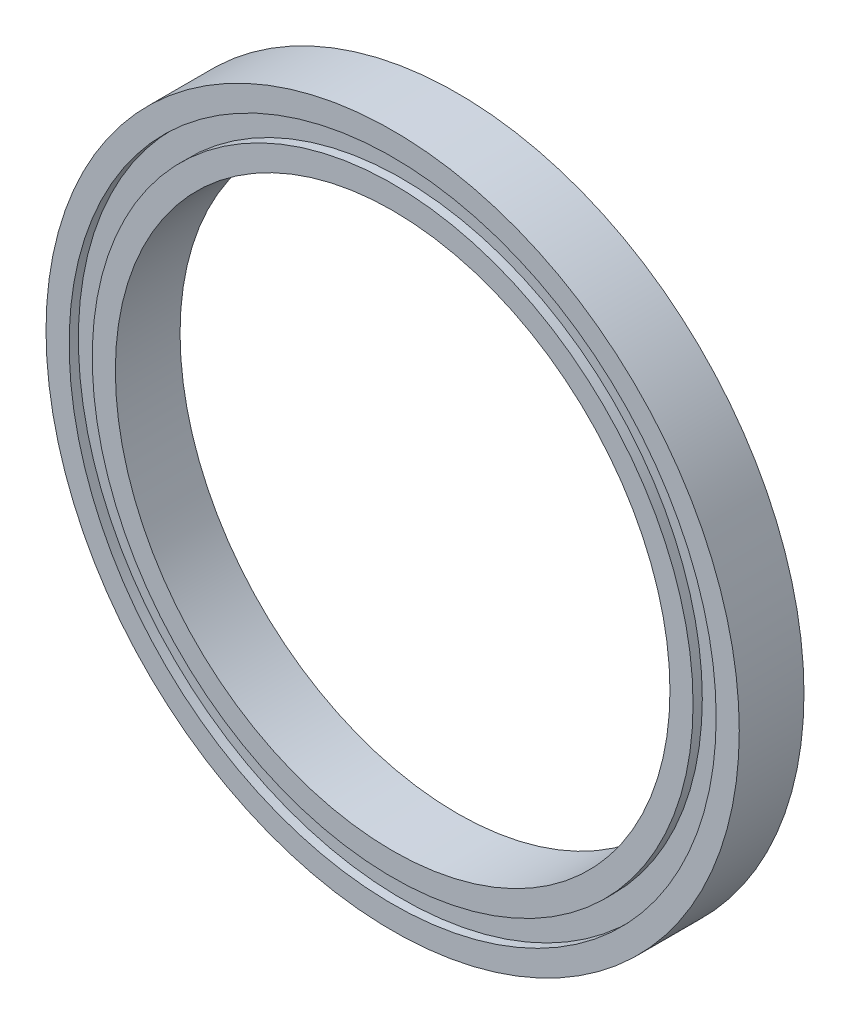
SolidWorks part; units mm, degrees
material "1023 碳钢板 (SS)"
ref_plane "前视基准面" through (0, 0, 0) normal (0, 0, 1) x (1, 0, 0)
ref_plane "上视基准面" through (0, 0, 0) normal (0, 1, 0) x (1, 0, 0)
ref_plane "右视基准面" through (0, 0, 0) normal (1, 0, 0) x (0, 0, -1)
other "Configuration Table"
sketch "草图1" plane through (0, 0, 0) normal (0, 0, 1) x (1, 0, 0)
  circle A0 centre (0, 0) radius 30
  circle A1 centre (0, 0) radius 37.5
  dimension "D1" = 60
  dimension "D2" = 75
extrude "凸台-拉伸1" add sketch "草图1" along normal blind 7
sketch "草图2" plane through (0, 0, 7) normal (0, 0, 1) x (1, 0, 0)
  circle A0 centre (0, 0) radius 32.5
  circle A1 centre (0, 0) radius 35
  circle A2 centre (0, 0) radius 30 construction
  circle A3 centre (0, 0) radius 37.5 construction
  dimension "D1" = 2.5
  dimension "D2" = 2.5
extrude "切除-拉伸1" cut sketch "草图2" against normal blind 1
sketch "草图3" plane through (0, 0, 0) normal (0, 0, -1) x (-1, 0, 0)
  circle A1 centre (0, 0) radius 32.5
  circle A2 centre (0, 0) radius 32.5
  circle A3 centre (0, 0) radius 35
  circle A4 centre (0, 0) radius 35
  dimension "D1" = 0
  dimension "D2" = 0
extrude "切除-拉伸2" cut sketch "草图3" against normal blind 1
